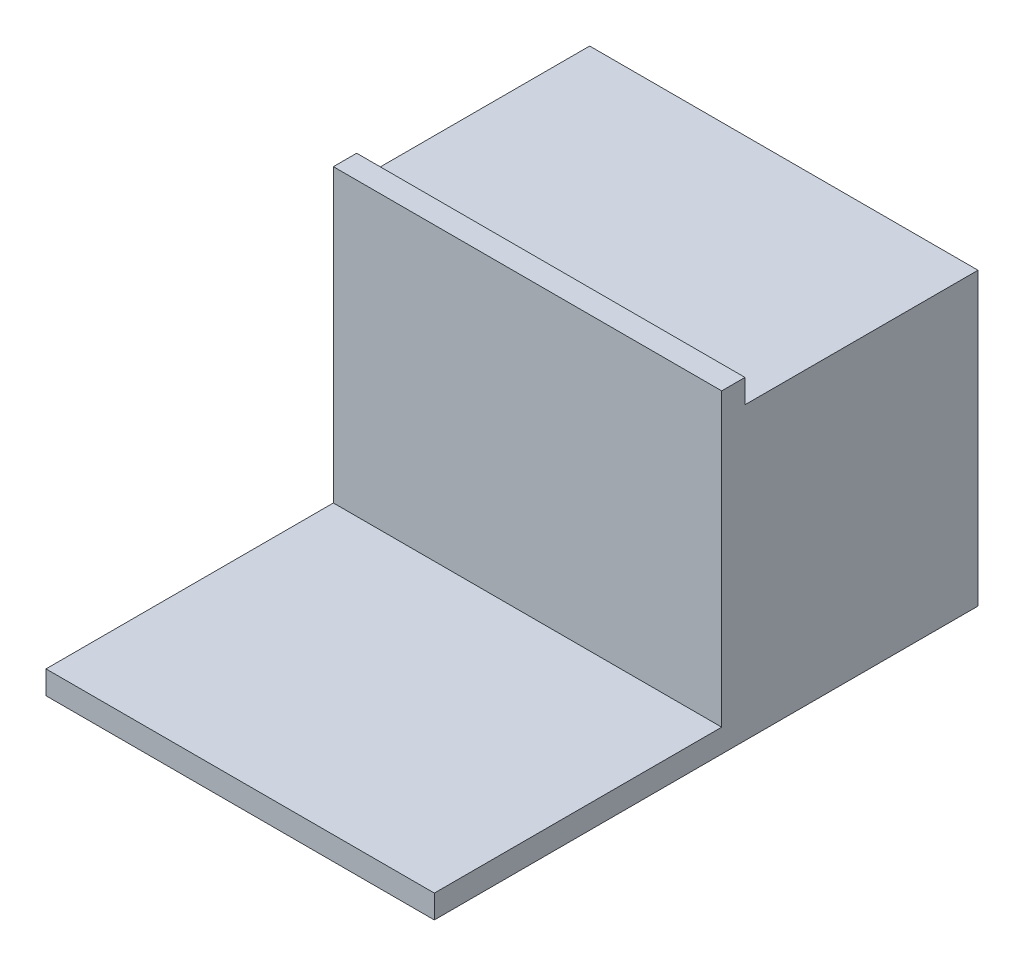
SolidWorks part; units mm, degrees
ref_plane "Alzado" through (0, 0, 0) normal (0, 0, 1) x (1, 0, 0)
ref_plane "Planta" through (0, 0, 0) normal (0, 1, 0) x (1, 0, 0)
ref_plane "Vista lateral" through (0, 0, 0) normal (1, 0, 0) x (0, 0, -1)
sketch "Croquis1" plane through (0, 0, 0) normal (0, 0, -1) x (-1, 0, 0)
  line L1 (0, 0) -> (5000, 0)
  line L2 (0, 0) -> (0, 3750)
  line L3 (0, 3750) -> (5000, 3750)
  line L4 (5000, 0) -> (5000, 3750)
  dimension "D1" = 5000
  dimension "D2" = 3750
extrude "Saliente-Extruir1" add sketch "Croquis1" against normal blind 300
sketch "Croquis2" plane through (0, 0, 0) normal (0, -1, 0) x (1, 0, 0)
  line L0 (-5000, 300) -> (-5000, 0) construction
  line L1 (0, 0) -> (-5000, 0)
  line L2 (0, 0) -> (0, 4000)
  line L3 (0, 4000) -> (-5000, 4000)
  line L4 (-5000, 0) -> (-5000, 4000)
  point P5 (-5289.8973, 0)
  dimension "D1" = 4000
extrude "Saliente-Extruir2" add sketch "Croquis2" along normal blind 300
sketch "Croquis3" plane through (0, 0, 0) normal (0, 0, -1) x (-1, 0, 0)
  line L0 (0, 3750) -> (0, -300) construction
  line L1 (0, 3445.2) -> (5000, 3445.2)
  line L2 (0, 3445.2) -> (0, -300)
  line L3 (0, -300) -> (5000, -300)
  line L4 (5000, 3445.2) -> (5000, -300)
  line L5 (5000, 3750) -> (0, 3750) construction
  dimension "D1" = 304.8
extrude "Saliente-Extruir3" add sketch "Croquis3" along normal blind 3000
